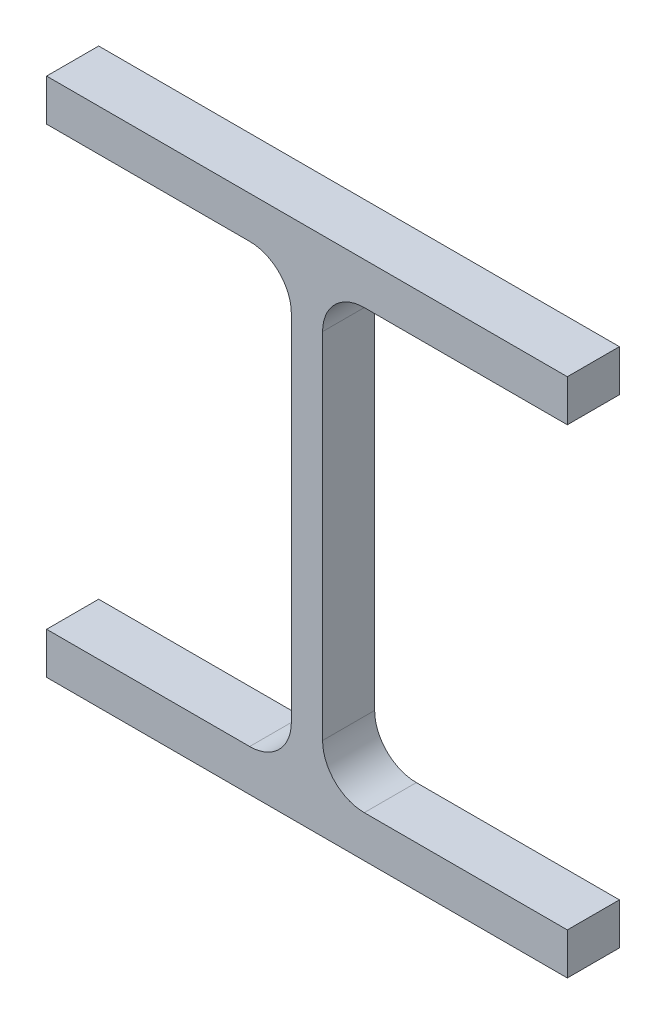
SolidWorks part; units mm, degrees
material "普通碳钢"
ref_plane "前视基准面" through (0, 0, 0) normal (0, 0, 1) x (1, 0, 0)
ref_plane "上视基准面" through (0, 0, 0) normal (0, 1, 0) x (1, 0, 0)
ref_plane "右视基准面" through (0, 0, 0) normal (1, 0, 0) x (0, 0, -1)
sketch "草图1" plane through (0, 0, 0) normal (0, 0, 1) x (1, 0, 0)
  line L0 (0, 58.6456) -> (0, -62.3376) construction
  line L1 (-61.3436, 0) -> (54.2436, 0) construction
  line L2 (50, 50) -> (-50, 50)
  line L3 (-50, 50) -> (-50, 42)
  line L4 (-50, 42) -> (-3, 42)
  line L5 (-3, 42) -> (-3, -42)
  line L6 (-50, -42) -> (-3, -42)
  line L7 (-50, -50) -> (-50, -42)
  line L8 (50, -50) -> (-50, -50)
  line L9 (3, 42) -> (3, -42)
  line L10 (50, 42) -> (3, 42)
  line L11 (50, 50) -> (50, 42)
  line L12 (50, -50) -> (50, -42)
  line L13 (50, -42) -> (3, -42)
  point P18 (0, 50)
  point P19 (0, -50)
  point P20 (0, 0)
  dimension "D1" = 100
  dimension "D2" = 100
  dimension "D3" = 6
  dimension "D4" = 8
extrude "凸台-拉伸1" add sketch "草图1" along normal blind 10
fillet "圆角1" radius 8 4 edges at (-3, -42, 5) (3, -42, 5) (3, 42, 5) (-3, 42, 5)
